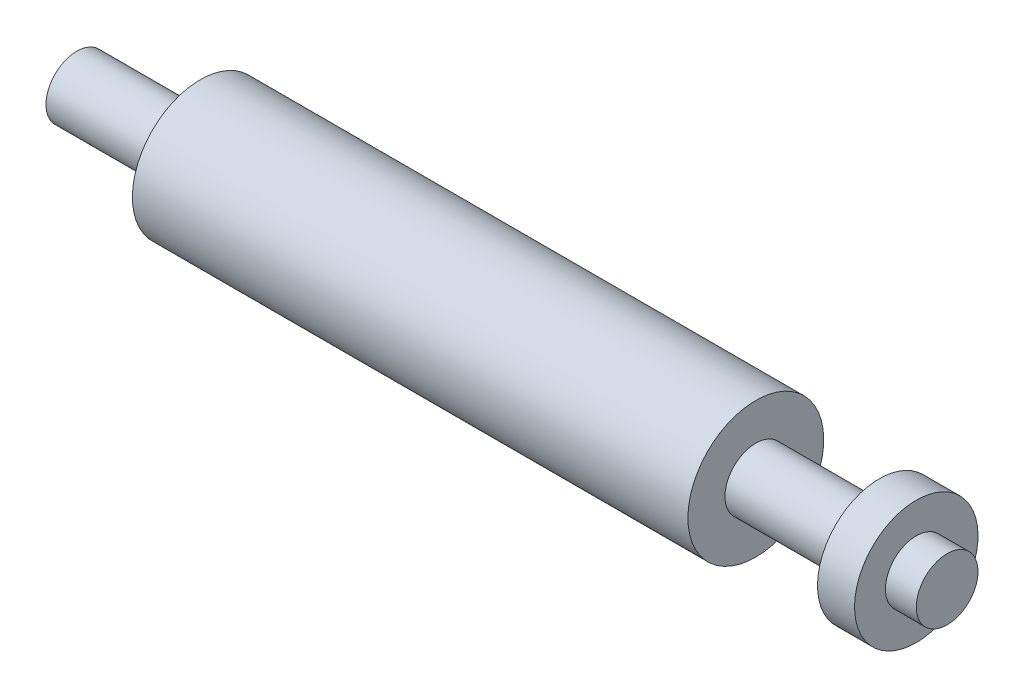
SolidWorks part; units mm, degrees
ref_plane "Front Plane" through (0, 0, 0) normal (0, 0, 1) x (1, 0, 0)
ref_plane "Top Plane" through (0, 0, 0) normal (0, 1, 0) x (1, 0, 0)
ref_plane "Right Plane" through (0, 0, 0) normal (1, 0, 0) x (0, 0, -1)
sketch "Sketch1" plane through (0, 0, 0) normal (0, 0, 1) x (1, 0, 0)
  line L0 (-330.0746, 0) -> (349.9254, 0)
  line L1 (349.9254, 0) -> (349.9254, 50)
  line L2 (349.9254, 50) -> (319.9254, 50)
  line L3 (319.9254, 50) -> (319.9254, 25)
  line L4 (319.9254, 25) -> (219.9254, 25)
  line L5 (219.9254, 25) -> (219.9254, 55)
  line L6 (219.9254, 55) -> (-230.0746, 55)
  line L7 (-230.0746, 55) -> (-230.0746, 25)
  line L8 (-230.0746, 25) -> (-330.0746, 25)
  line L9 (-330.0746, 25) -> (-330.0746, 0)
  line L10 (349.9254, 25) -> (374.9254, 25)
  line L11 (374.9254, 25) -> (374.9254, 0)
  line L12 (374.9254, 0) -> (349.9254, 0)
  dimension "D1" = 450
  dimension "D2" = 25
  dimension "D3" = 30
  dimension "D4" = 100
  dimension "D5" = 30
  dimension "D6" = 100
  dimension "D7" = 30
  dimension "D8" = 50
  dimension "D9" = 25
  dimension "D10" = 25
revolve "Revolve1" add sketch "Sketch1" angle 360 about L0
